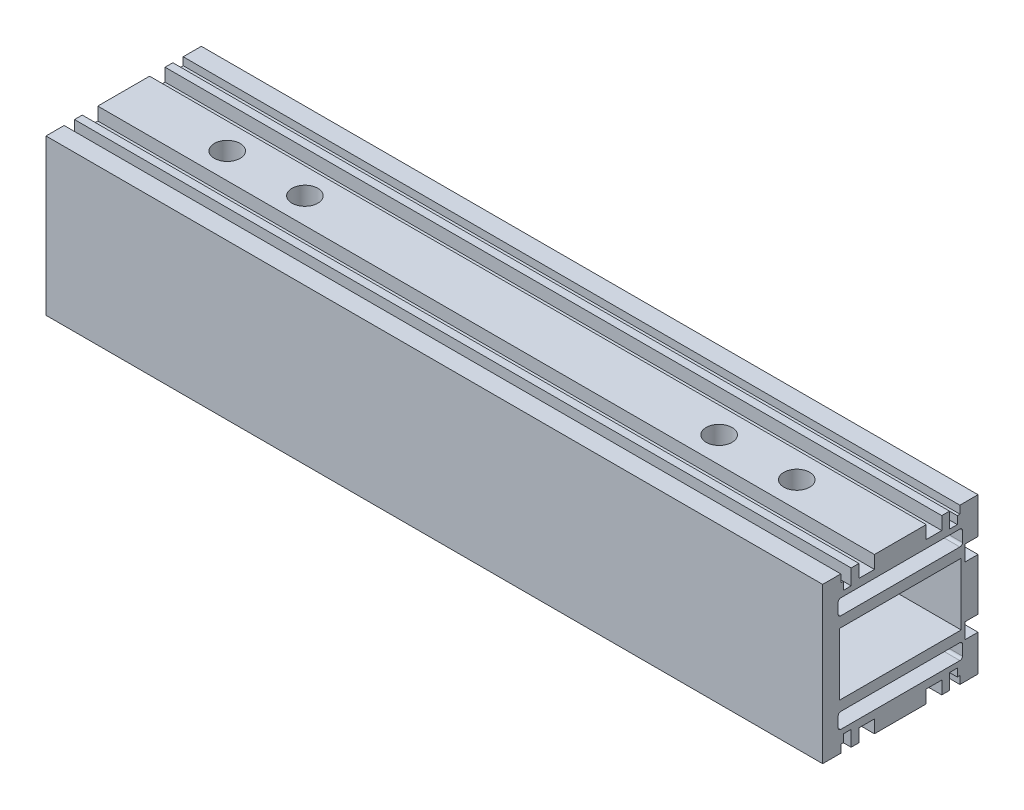
SolidWorks part; units mm, degrees
ref_plane "前视基准面" through (0, 0, 0) normal (0, 0, 1) x (1, 0, 0)
ref_plane "上视基准面" through (0, 0, 0) normal (0, 1, 0) x (1, 0, 0)
ref_plane "右视基准面" through (0, 0, 0) normal (1, 0, 0) x (0, 0, -1)
sketch "草图1" plane through (0, 0, 0) normal (1, 0, 0) x (0, 0, -1)
  line L0 (-15, 15) -> (15, -15) construction
  line L1 (-15, 15) -> (-11.5, 15)
  line L2 (-15, 15) -> (-15, -15)
  line L3 (-15, -15) -> (-11.5, -15)
  line L4 (15, 15) -> (15, 8)
  line L5 (15, 15) -> (-15, -15) construction
  line L6 (-11.5, 15) -> (-11.5, 13.5)
  line L7 (-11.5, 13.5) -> (-11, 13.5)
  line L8 (-11, 13.5) -> (-11, 12)
  line L9 (-11, 12) -> (-9.5, 12)
  line L10 (-9.5, 12) -> (-9.5, 15)
  line L11 (-9.5, 15) -> (-8, 15)
  line L12 (-8, 15) -> (-8, 12.5)
  line L13 (-8, 12.5) -> (-5, 12.5)
  line L14 (-5, 12.5) -> (-5, 15)
  line L15 (-5, 15) -> (5, 15)
  line L16 (0, 21.5201) -> (0, -18.309) construction
  line L17 (0, 55) -> (0, -55) construction
  line L18 (5, 12.5) -> (5, 15)
  line L19 (8, 12.5) -> (5, 12.5)
  line L20 (8, 15) -> (8, 12.5)
  line L21 (9.5, 15) -> (8, 15)
  line L22 (9.5, 12) -> (9.5, 15)
  line L23 (11, 12) -> (9.5, 12)
  line L24 (11, 13.5) -> (11, 12)
  line L25 (11.5, 13.5) -> (11, 13.5)
  line L26 (11.5, 15) -> (11.5, 13.5)
  line L27 (8, 15) -> (9.5, 15)
  line L28 (11.5, 15) -> (15, 15)
  line L29 (-19.8303, 0) -> (22.13, 0) construction
  line L30 (55, 0) -> (-55, 0) construction
  line L31 (8, -15) -> (9.5, -15)
  line L32 (11.5, -15) -> (11.5, -13.5)
  line L33 (11.5, -13.5) -> (11, -13.5)
  line L34 (11, -13.5) -> (11, -12)
  line L35 (11, -12) -> (9.5, -12)
  line L36 (9.5, -12) -> (9.5, -15)
  line L37 (9.5, -15) -> (8, -15)
  line L38 (8, -15) -> (8, -12.5)
  line L39 (8, -12.5) -> (5, -12.5)
  line L40 (5, -12.5) -> (5, -15)
  line L41 (-5, -15) -> (5, -15)
  line L42 (-5, -12.5) -> (-5, -15)
  line L43 (-8, -12.5) -> (-5, -12.5)
  line L44 (-8, -15) -> (-8, -12.5)
  line L45 (-9.5, -15) -> (-8, -15)
  line L46 (-9.5, -12) -> (-9.5, -15)
  line L47 (-11, -12) -> (-9.5, -12)
  line L48 (-11, -13.5) -> (-11, -12)
  line L49 (-11.5, -13.5) -> (-11, -13.5)
  line L50 (-11.5, -15) -> (-11.5, -13.5)
  line L51 (-9.5, -15) -> (-8, -15)
  line L52 (-5, -15) -> (5, -15)
  line L53 (8, -15) -> (9.5, -15)
  line L54 (11.5, -15) -> (15, -15)
  line L55 (15, 8) -> (12.5, 8)
  line L56 (12.5, 8) -> (12.5, 5)
  line L57 (12.5, 5) -> (15, 5)
  line L58 (12.5, -5) -> (15, -5)
  line L59 (12.5, -8) -> (12.5, -5)
  line L60 (15, -8) -> (12.5, -8)
  line L61 (15, 5) -> (15, -5)
  line L62 (15, -8) -> (15, -15)
  line L63 (12, -10.5) -> (12, -8.5)
  line L64 (-11.5, 11) -> (11.5, 11)
  line L65 (-12, 10.5) -> (-12, 8.5)
  line L66 (-11.5, 8) -> (11.5, 8)
  line L67 (12, 10.5) -> (12, 8.5)
  line L68 (-11.5, -8) -> (11.5, -8)
  line L69 (-12, -10.5) -> (-12, -8.5)
  line L70 (-11.5, -11) -> (11.5, -11)
  line L72 (-11.75, 6) -> (11.75, 6)
  line L73 (-11.75, 6) -> (-11.75, -6)
  line L74 (-11.75, -6) -> (11.75, -6)
  line L75 (11.75, 6) -> (11.75, -6)
  arc A0 (12, 8.5) -> (11.5, 8) centre (11.5, 8.5) cw
  arc A1 (11.5, 11) -> (12, 10.5) centre (11.5, 10.5) cw
  arc A2 (-11.5, 11) -> (-12, 10.5) centre (-11.5, 10.5) ccw
  arc A3 (-11.5, 8) -> (-12, 8.5) centre (-11.5, 8.5) cw
  arc A8 (-11.5, -8) -> (-12, -8.5) centre (-11.5, -8.5) ccw
  arc A9 (-11.5, -11) -> (-12, -10.5) centre (-11.5, -10.5) cw
  arc A10 (11.5, -11) -> (12, -10.5) centre (11.5, -10.5) ccw
  arc A11 (12, -8.5) -> (11.5, -8) centre (11.5, -8.5) ccw
  point P69 (12, 11)
  point P72 (-12, 11)
  point P77 (-11, -13.5)
  point P80 (11, -13.5)
  point P83 (11, 13.5)
  point P86 (-11, 13.5)
  point P99 (-12, -11)
  point P100 (12, -11)
  dimension "D17" = 0.5
  dimension "D1" = 3.5
  dimension "D2" = 1.5
  dimension "D3" = 0.5
  dimension "D4" = 1.5
  dimension "D5" = 3
  dimension "D6" = 30
  dimension "D7" = 30
  dimension "D8" = 1.5
  dimension "D9" = 2.5
  dimension "D10" = 3
  dimension "D11" = 2.5
  dimension "D12" = 7
  dimension "D13" = 3
  dimension "D14" = 4
  dimension "D15" = 3
  dimension "D16" = 24
  dimension "D19" = 23.5
  dimension "D20" = 12
extrude "凸台-拉伸1" add sketch "草图1" along normal mid plane 150
hole_wizard "M6 螺纹孔1" positions "草图3" profile "草图2" tap size "M6" standard "GB"
sketch "草图3" plane through (0, 15, 0) normal (0, 1, 0) x (1, 0, 0)
  point P0 (-40, 0)
  point P3 (-55, 0)
  point P6 (55, 0)
  point P9 (40, 0)
sketch "草图2" plane through (-40, 15, 0) normal (1, 0, 0) x (0, 0, 1)
  line L0 (0, 0) -> (0, 20.5022)
  line L1 (0, 20.5022) -> (2.5, 19)
  line L2 (2.5, 19) -> (2.5, 0)
  line L5 (2.5, 0) -> (0, 0)
  line L10 (0, 20.5022) -> (-2.5, 19) construction
  line L11 (0, -6.35) -> (0, 107.95) construction
  dimension "螺纹孔钻头直径" = 5
  dimension "螺纹孔钻头深度" = 19
  dimension "导头角度" = 118
cosmetic thread "孔螺蚊线1" parameters "D1"=9, "D2"=6
cosmetic thread "孔螺蚊线2" parameters "D1"=9, "D2"=6
cosmetic thread "孔螺蚊线3" parameters "D1"=9, "D2"=6
cosmetic thread "孔螺蚊线4" parameters "D1"=9, "D2"=6
hole_wizard "M6 螺纹孔2" positions "草图5" profile "草图4" tap size "M6" standard "GB"
sketch "草图5" plane through (0, -15, 0) normal (0, -1, 0) x (-1, 0, 0)
  line L0 (-75, 15) -> (75, 15) construction
  line L1 (-75, -5) -> (-75, 5) construction
  line L2 (-75, 15) -> (75, 15) construction
  line L3 (75, -5) -> (75, 5) construction
  point P0 (-39, 0)
  point P2 (39, 0)
  dimension "D1" = 15
  dimension "D2" = 36
  dimension "D3" = 15
  dimension "D4" = 36
sketch "草图4" plane through (39, -15, 0) normal (1, 0, 0) x (0, 0, -1)
  line L0 (0, 0) -> (0, 20.5022)
  line L1 (0, 20.5022) -> (2.5, 19)
  line L2 (2.5, 19) -> (2.5, 0)
  line L5 (2.5, 0) -> (0, 0)
  line L10 (0, 20.5022) -> (-2.5, 19) construction
  line L11 (0, -6.35) -> (0, 107.95) construction
  dimension "螺纹孔钻头直径" = 5
  dimension "螺纹孔钻头深度" = 19
  dimension "导头角度" = 118
cosmetic thread "孔螺蚊线5" parameters "D1"=9, "D2"=6
cosmetic thread "孔螺蚊线6" parameters "D1"=9, "D2"=6
